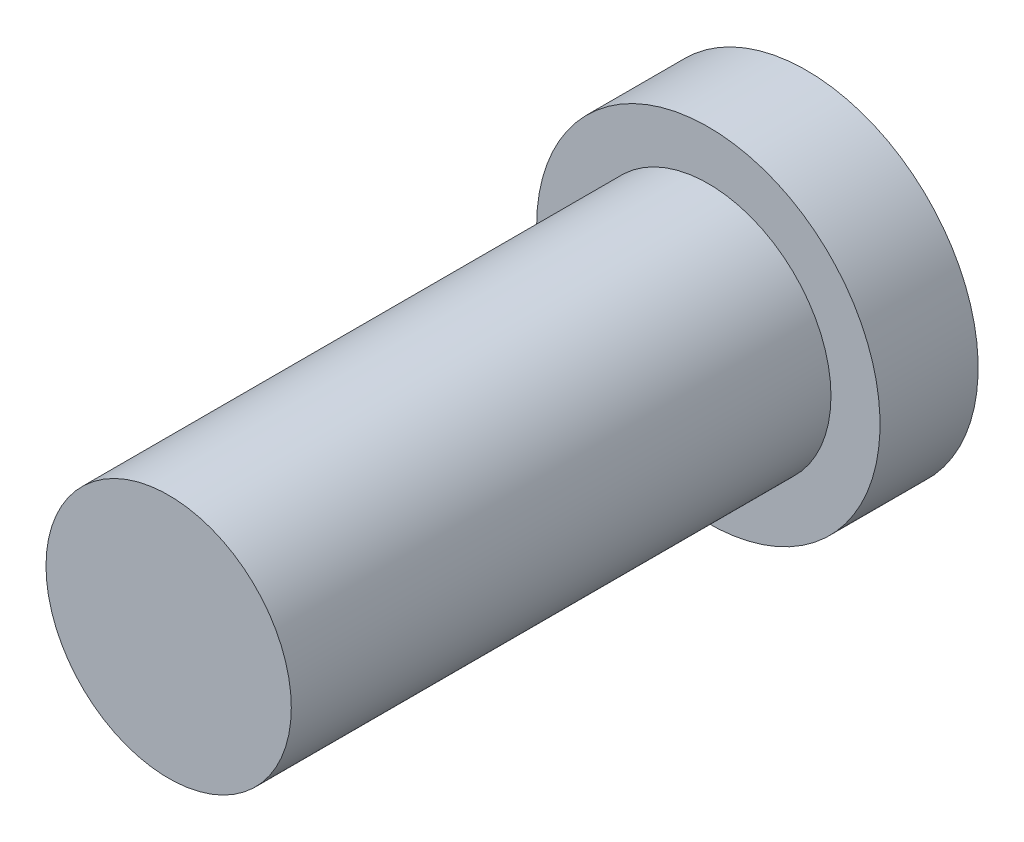
SolidWorks part; units mm, degrees
ref_plane "Plano frontal" through (0, 0, 0) normal (0, 0, 1) x (1, 0, 0)
ref_plane "Plano superior" through (0, 0, 0) normal (0, 1, 0) x (1, 0, 0)
ref_plane "Plano direito" through (0, 0, 0) normal (1, 0, 0) x (0, 0, -1)
sketch "Esboço1" plane through (0, 0, 0) normal (0, 0, 1) x (1, 0, 0)
  circle A0 centre (0, 0) radius 5
extrude "Ressalto-extrusão1" add sketch "Esboço1" along normal blind 22
sketch "Esboço2" plane through (0, 0, 0) normal (0, 0, -1) x (-1, 0, 0)
  circle A0 centre (0, 0) radius 7
extrude "Ressalto-extrusão2" add sketch "Esboço2" along normal blind 4
